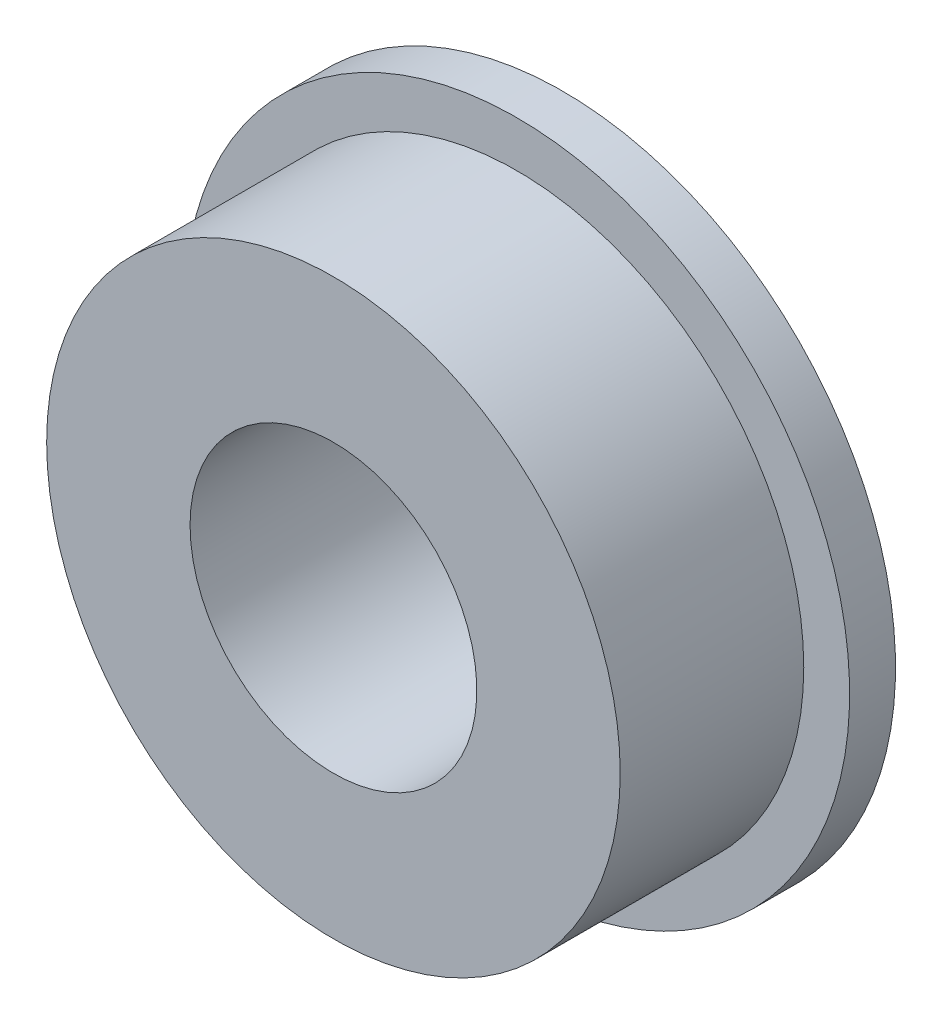
SolidWorks part; units mm, degrees
material "1.5714 (16NiCr4)"
ref_plane "前视基准面" through (0, 0, 0) normal (0, 0, 1) x (1, 0, 0)
ref_plane "上视基准面" through (0, 0, 0) normal (0, 1, 0) x (1, 0, 0)
ref_plane "右视基准面" through (0, 0, 0) normal (1, 0, 0) x (0, 0, -1)
sketch "草图1" plane through (0, 0, 0) normal (0, 0, 1) x (1, 0, 0)
  circle A0 centre (0, 0) radius 5
  dimension "D1" = 10
extrude "凸台-拉伸1" add sketch "草图1" along normal blind 4
sketch "草图2" plane through (0, 0, 0) normal (0, 0, -1) x (-1, 0, 0)
  circle A0 centre (0, 0) radius 5.8
  dimension "D1" = 11.6
extrude "凸台-拉伸2" add sketch "草图2" against normal blind 0.8
sketch "草图3" plane through (0, 0, 0) normal (0, 0, -1) x (-1, 0, 0)
  circle A0 centre (0, 0) radius 2.5
  dimension "D1" = 5
extrude "切除-拉伸1" cut sketch "草图3" against normal through all
equation "\"内径d\"= 5"
equation "\"外径D\"= 10"
equation "\"法兰外径D1\"= 11.6"
equation "\"轴承宽度B\"= 4"
equation "\"法兰宽度C1\"= 0.8"
equation "\"D1@草图1\"=\"外径D\""
equation "\"D1@凸台-拉伸1\"=\"轴承宽度B\""
equation "\"D1@草图2\"=\"法兰外径D1\""
equation "\"D1@凸台-拉伸2\"=\"法兰宽度C1\""
equation "\"D1@草图3\"=\"内径d\""
